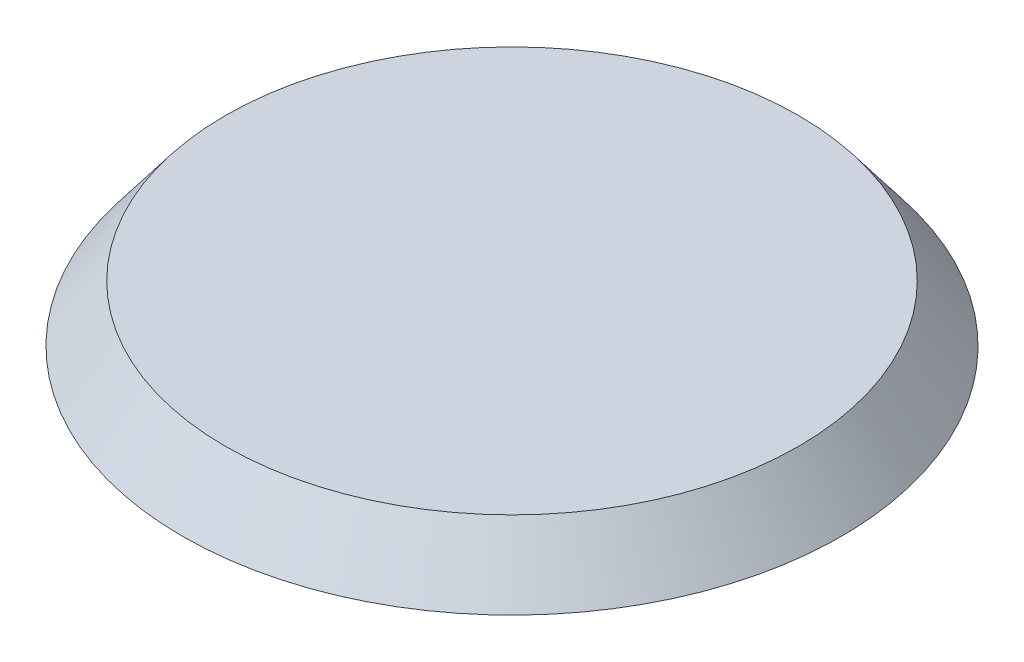
SolidWorks part; units mm, degrees
material "Glass"
ref_plane "Front Plane" through (0, 0, 0) normal (0, 0, 1) x (1, 0, 0)
ref_plane "Top Plane" through (0, 0, 0) normal (0, 1, 0) x (1, 0, 0)
ref_plane "Right Plane" through (0, 0, 0) normal (1, 0, 0) x (0, 0, -1)
sketch "Sketch1" plane through (0, 0, 0) normal (1, 0, 0) x (0, 0, -1)
  line L0 (0, 0) -> (0, 44.3337) construction
  line L1 (0, 33.5414) -> (-25.4, 33.5414)
  line L2 (-25.4, 33.5414) -> (-29.21, 28.5414)
  line L3 (-29.21, 28.5414) -> (0, 28.5414)
  line L4 (0, 33.5414) -> (0, 28.5414)
  dimension "D1" = 5
  dimension "D2" = 50.8
  dimension "D3" = 58.42
revolve "Revolve1" add sketch "Sketch1" angle 360 about L0
